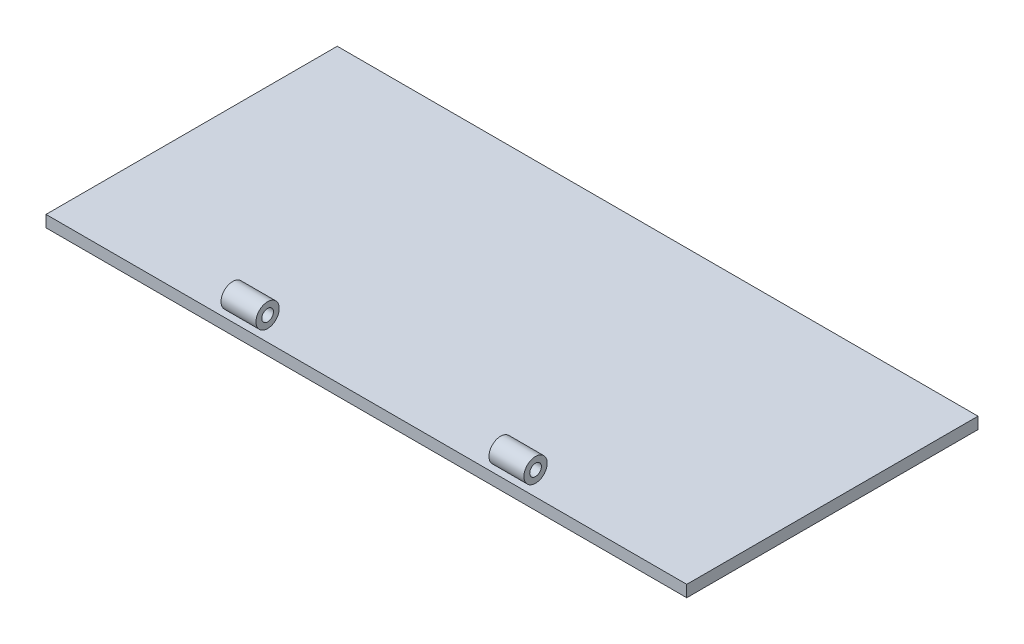
SolidWorks part; units mm, degrees
ref_plane "Front Plane" through (0, 0, 0) normal (0, 0, 1) x (1, 0, 0)
ref_plane "Top Plane" through (0, 0, 0) normal (0, 1, 0) x (1, 0, 0)
ref_plane "Right Plane" through (0, 0, 0) normal (1, 0, 0) x (0, 0, -1)
sketch "Sketch1" plane through (0, 0, 0) normal (1, 0, 0) x (0, 0, -1)
  line L1 (-93.515, 17.7098) -> (156.485, 17.7098)
  line L2 (-93.515, 17.7098) -> (-93.515, 7.7098)
  line L3 (-93.515, 7.7098) -> (156.485, 7.7098)
  line L4 (156.485, 17.7098) -> (156.485, 7.7098)
  circle A0 centre (-83.2935, 27.7098) radius 10
  dimension "D2" = 20
  dimension "D1" = 250
  dimension "D3" = 10
extrude "Boss-Extrude3" add sketch "Sketch1" along normal blind 550 contours A0 | L4 L1 L2 L3
sketch "Sketch5" plane through (550, 0, 0) normal (1, 0, 0) x (0, 0, -1)
  circle A0 centre (-83.2935, 27.7098) radius 10
extrude "Cut-Extrude3" cut sketch "Sketch5" against normal blind 140
sketch "Sketch6" plane through (0, 0, 0) normal (-1, 0, 0) x (0, 0, 1)
  circle A0 centre (83.2935, 27.7098) radius 10
extrude "Cut-Extrude4" cut sketch "Sketch6" against normal blind 380
sketch "Sketch7" plane through (380, 0, 0) normal (-1, 0, 0) x (0, 0, 1)
  circle A0 centre (83.2935, 27.7098) radius 5
  dimension "D1" = 10
extrude "Cut-Extrude5" cut sketch "Sketch7" against normal blind 380
sketch "Sketch8" plane through (0, 0, 0) normal (-1, 0, 0) x (0, 0, 1)
  circle A0 centre (83.2935, 27.7098) radius 10
extrude "Boss-Extrude5" add sketch "Sketch8" against normal blind 180 separate body
sketch "Sketch10" plane through (0, 0, 0) normal (-1, 0, 0) x (0, 0, 1)
  circle A0 centre (83.2935, 27.7098) radius 10
extrude "Cut-Extrude6" cut sketch "Sketch10" against normal blind 150
sketch "Sketch11" plane through (150, 0, 0) normal (-1, 0, 0) x (0, 0, 1)
  circle A0 centre (83.2935, 27.7098) radius 5
  dimension "D1" = 10
extrude "Cut-Extrude7" cut sketch "Sketch11" against normal blind 150
